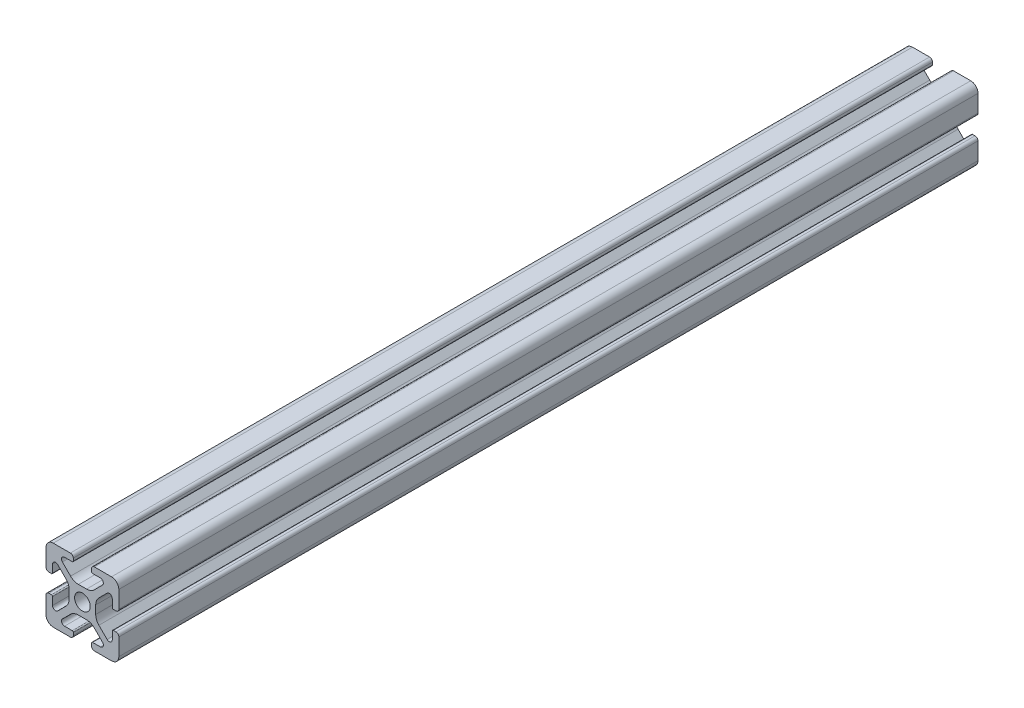
SolidWorks part; units mm, degrees
material "Alliage 1060"
ref_plane "Plan de face" through (0, 0, 0) normal (0, 0, 1) x (1, 0, 0)
ref_plane "Plan de dessus" through (0, 0, 0) normal (0, 1, 0) x (1, 0, 0)
ref_plane "Plan de droite" through (0, 0, 0) normal (1, 0, 0) x (0, 0, -1)
ref_plane "Plan1" through (0, 0, 0) normal (0, 0, -1) x (-1, 0, 0)
sketch "Esquisse1" plane through (0, 0, 0) normal (0, 0, -1) x (-1, 0, 0)
  line L0 (-18, 0) -> (-13.3, 0)
  line L1 (-12.8, 1.8) -> (-14.9184, 1.8)
  line L2 (-15.5064, 3.2196) -> (-13.2547, 5.4713)
  line L3 (-11.1334, 6.35) -> (-8.8666, 6.35)
  line L4 (-6.7453, 5.4713) -> (-4.4936, 3.2196)
  line L5 (-5.0816, 1.8) -> (-7.2, 1.8)
  line L6 (-6.7, 0) -> (-2, 0)
  line L7 (0, 2) -> (0, 6.7)
  line L8 (-1.8, 7.2) -> (-1.8, 5.0816)
  line L9 (-3.2196, 4.4936) -> (-5.4713, 6.7453)
  line L10 (-6.35, 8.8666) -> (-6.35, 11.1334)
  line L11 (-5.4713, 13.2547) -> (-3.2196, 15.5064)
  line L12 (-1.8, 14.9184) -> (-1.8, 12.8)
  line L13 (0, 13.3) -> (0, 18)
  line L14 (-2, 20) -> (-6.7, 20)
  line L15 (-7.2, 18.2) -> (-5.0816, 18.2)
  line L16 (-4.4936, 16.7804) -> (-6.7453, 14.5287)
  line L17 (-8.8666, 13.65) -> (-11.1334, 13.65)
  line L18 (-13.2547, 14.5287) -> (-15.5064, 16.7804)
  line L19 (-14.9184, 18.2) -> (-12.8, 18.2)
  line L20 (-13.3, 20) -> (-18, 20)
  line L21 (-20, 18) -> (-20, 13.3)
  line L22 (-16.7804, 15.5064) -> (-14.5287, 13.2547)
  line L23 (-13.65, 11.1334) -> (-13.65, 8.8666)
  line L24 (-14.5287, 6.7453) -> (-16.7804, 4.4936)
  line L25 (-18.2, 5.0816) -> (-18.2, 7.2)
  line L26 (-20, 6.7) -> (-20, 2)
  arc A0 (-20, 2) -> (-18, 0) centre (-18, 2) ccw
  arc A1 (-13.3, 0) -> (-12.5, 0.8) centre (-13.3, 0.8) ccw
  arc A2 (-12.5, 1.5) -> (-12.8, 1.8) centre (-12.8, 1.5) ccw
  arc A3 (-14.9184, 1.8) -> (-15.5064, 3.2196) centre (-14.9184, 2.6316) cw
  arc A4 (-13.2547, 5.4713) -> (-11.1334, 6.35) centre (-11.1334, 3.35) cw
  arc A5 (-8.8666, 6.35) -> (-6.7453, 5.4713) centre (-8.8666, 3.35) cw
  arc A6 (-4.4936, 3.2196) -> (-5.0816, 1.8) centre (-5.0816, 2.6316) cw
  arc A7 (-7.2, 1.8) -> (-7.5, 1.5) centre (-7.2, 1.5) ccw
  arc A8 (-7.5, 0.8) -> (-6.7, 0) centre (-6.7, 0.8) ccw
  arc A9 (-2, 0) -> (0, 2) centre (-2, 2) ccw
  arc A10 (0, 6.7) -> (-0.8, 7.5) centre (-0.8, 6.7) ccw
  arc A11 (-1.5, 7.5) -> (-1.8, 7.2) centre (-1.5, 7.2) ccw
  arc A12 (-1.8, 5.0816) -> (-3.2196, 4.4936) centre (-2.6316, 5.0816) cw
  arc A13 (-5.4713, 6.7453) -> (-6.35, 8.8666) centre (-3.35, 8.8666) cw
  arc A14 (-6.35, 11.1334) -> (-5.4713, 13.2547) centre (-3.35, 11.1334) cw
  arc A15 (-3.2196, 15.5064) -> (-1.8, 14.9184) centre (-2.6316, 14.9184) cw
  arc A16 (-1.8, 12.8) -> (-1.5, 12.5) centre (-1.5, 12.8) ccw
  arc A17 (-0.8, 12.5) -> (0, 13.3) centre (-0.8, 13.3) ccw
  arc A18 (0, 18) -> (-2, 20) centre (-2, 18) ccw
  arc A19 (-6.7, 20) -> (-7.5, 19.2) centre (-6.7, 19.2) ccw
  arc A20 (-7.5, 18.5) -> (-7.2, 18.2) centre (-7.2, 18.5) ccw
  arc A21 (-5.0816, 18.2) -> (-4.4936, 16.7804) centre (-5.0816, 17.3684) cw
  arc A22 (-6.7453, 14.5287) -> (-8.8666, 13.65) centre (-8.8666, 16.65) cw
  arc A23 (-11.1334, 13.65) -> (-13.2547, 14.5287) centre (-11.1334, 16.65) cw
  arc A24 (-15.5064, 16.7804) -> (-14.9184, 18.2) centre (-14.9184, 17.3684) cw
  arc A25 (-12.8, 18.2) -> (-12.5, 18.5) centre (-12.8, 18.5) ccw
  arc A26 (-12.5, 19.2) -> (-13.3, 20) centre (-13.3, 19.2) ccw
  arc A27 (-18, 20) -> (-20, 18) centre (-18, 18) ccw
  arc A28 (-20, 13.3) -> (-19.2, 12.5) centre (-19.2, 13.3) ccw
  arc A29 (-18.5, 12.5) -> (-18.2, 12.8) centre (-18.5, 12.8) ccw
  arc A30 (-18.2, 14.9184) -> (-16.7804, 15.5064) centre (-17.3684, 14.9184) cw
  arc A31 (-14.5287, 13.2547) -> (-13.65, 11.1334) centre (-16.65, 11.1334) cw
  arc A32 (-13.65, 8.8666) -> (-14.5287, 6.7453) centre (-16.65, 8.8666) cw
  arc A33 (-16.7804, 4.4936) -> (-18.2, 5.0816) centre (-17.3684, 5.0816) cw
  arc A34 (-18.2, 7.2) -> (-18.5, 7.5) centre (-18.5, 7.2) ccw
  arc A35 (-19.2, 7.5) -> (-20, 6.7) centre (-19.2, 6.7) ccw
  circle A36 centre (-10, 10) radius 2.15
  spline S0 degree 1 poles (-12.5, 1.5) (-12.5, 0.8) knots 0 0 0.7 0.7
  spline S1 degree 1 poles (-7.5, 0.8) (-7.5, 1.5) knots 0 0 0.7 0.7
  spline S2 degree 1 poles (-1.5, 7.5) (-0.8, 7.5) knots 0 0 0.7 0.7
  spline S3 degree 1 poles (-0.8, 12.5) (-1.5, 12.5) knots 0 0 0.7 0.7
  spline S4 degree 1 poles (-7.5, 18.5) (-7.5, 19.2) knots 0 0 0.7 0.7
  spline S5 degree 1 poles (-12.5, 19.2) (-12.5, 18.5) knots 0 0 0.7 0.7
  spline S6 degree 1 poles (-18.5, 12.5) (-19.2, 12.5) knots 0 0 0.7 0.7
  spline S7 degree 1 poles (-18.2, 14.9184) (-18.2, 12.8) knots 0 0 2.118424 2.118424
  spline S8 degree 1 poles (-19.2, 7.5) (-18.5, 7.5) knots 0 0 0.7 0.7
extrude "Extrusion1" add sketch "Esquisse1" against normal blind 236
